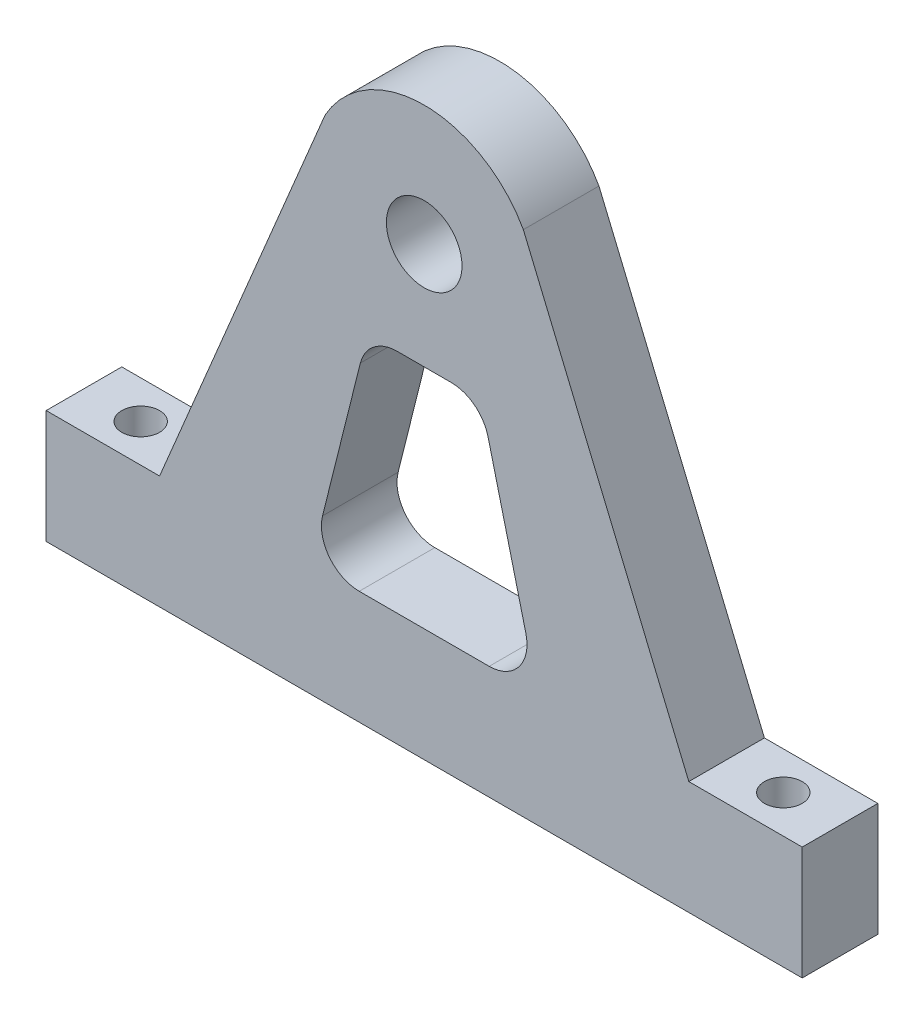
SolidWorks part; units mm, degrees
ref_plane "Front Plane" through (0, 0, 0) normal (0, 0, 1) x (1, 0, 0)
ref_plane "Top Plane" through (0, 0, 0) normal (0, 1, 0) x (1, 0, 0)
ref_plane "Right Plane" through (0, 0, 0) normal (1, 0, 0) x (0, 0, -1)
sketch "Sketch1" plane through (0, 0, 0) normal (0, 0, 1) x (1, 0, 0)
  line L0 (0, 0) -> (0, 59.06) construction
  line L1 (35, 15) -> (13.115, 67.2799)
  line L2 (50, 15) -> (35, 15)
  line L3 (-35, 15) -> (-13.115, 67.2799)
  line L4 (50, 0) -> (50, 15)
  line L5 (35, 0) -> (50, 0)
  line L6 (-35, 0) -> (-50, 0)
  line L7 (-50, 0) -> (-50, 15)
  line L8 (-50, 15) -> (-35, 15)
  line L9 (35, 0) -> (-35, 0)
  circle A0 centre (0, 59.06) radius 5
  arc A1 (13.115, 67.2799) -> (-13.115, 67.2799) centre (0, 60) ccw
extrude "Boss-Extrude2" add sketch "Sketch1" along normal blind 10
sketch "Sketch3" plane through (0, 0, 0) normal (0, 0, -1) x (-1, 0, 0)
  line L0 (0, 0) -> (0, 15) construction
  line L1 (0, 15) -> (-8.5961, 15)
  line L2 (0, 15) -> (8.5961, 15)
  line L3 (0, 15) -> (0, 45) construction
  line L4 (13.4468, 21.2127) -> (8.4468, 41.2127)
  line L5 (3.5961, 45) -> (0, 45)
  line L6 (0, 45) -> (-3.5961, 45)
  line L7 (-8.4468, 41.2127) -> (-13.4468, 21.2127)
  arc A0 (8.4468, 41.2127) -> (3.5961, 45) centre (3.5961, 40) ccw
  arc A1 (-3.5961, 45) -> (-8.4468, 41.2127) centre (-3.5961, 40) ccw
  arc A2 (-13.4468, 21.2127) -> (-8.5961, 15) centre (-8.5961, 20) ccw
  arc A3 (8.5961, 15) -> (13.4468, 21.2127) centre (8.5961, 20) ccw
  dimension "D1" = 5
extrude "Cut-Extrude1" cut sketch "Sketch3" against normal blind 25
sketch "Sketch4" plane through (0, 15, 0) normal (0, 1, 0) x (1, 0, 0)
  line L0 (-50, -5) -> (-42.5, -5) construction
  line L1 (-50, -10) -> (-50, 0) construction
  line L2 (0, 0) -> (0, 1.7601) construction
  circle A0 centre (-42.5, -5) radius 2.5
  circle A1 centre (42.5, -5) radius 2.5
extrude "Cut-Extrude2" cut sketch "Sketch4" against normal blind 38
